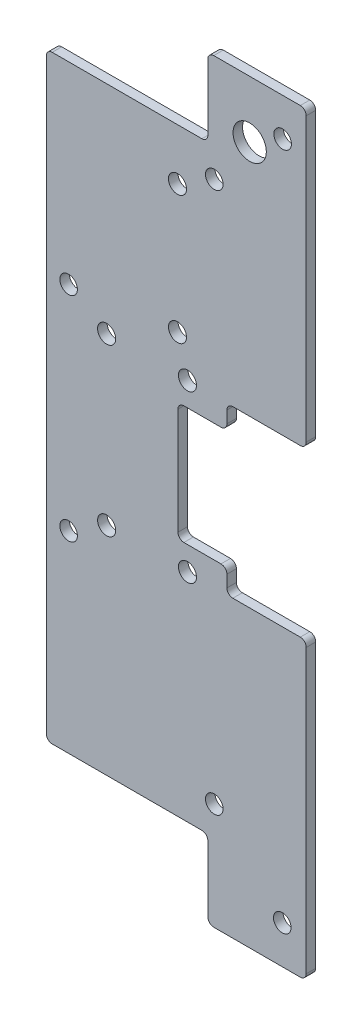
SolidWorks part; units mm, degrees
material "Thornel Mat VMA"
ref_plane "Front Plane" through (0, 0, 0) normal (0, 0, 1) x (1, 0, 0)
ref_plane "Top Plane" through (0, 0, 0) normal (0, 1, 0) x (1, 0, 0)
ref_plane "Right Plane" through (0, 0, 0) normal (1, 0, 0) x (0, 0, -1)
sketch "Sketch1" plane through (0, 0, 0) normal (0, 0, 1) x (1, 0, 0)
  line L0 (-2.9301, -104.5098) -> (-3.3149, -104.5098)
  line L1 (-3.3149, -72.8868) -> (-2.9301, -72.8868)
  line L78 (45.3299, -66.5368) -> (45.3299, -72.8868)
  line L79 (45.3299, -104.5098) -> (45.3299, -110.8598)
  line L80 (66.5174, -66.5368) -> (105.3971, 12.1397)
  line L81 (105.3971, 12.1397) -> (38.7094, 12.1397)
  line L88 (38.7094, 12.1397) -> (38.7094, -8.6883)
  line L89 (-2.9301, -8.6883) -> (38.7094, -8.6883)
  line L90 (-3.3149, -53.8368) -> (-2.9301, -53.8368)
  line L91 (-2.9301, -53.8368) -> (-2.9301, -8.6883)
  line L92 (-3.3149, -66.5368) -> (-3.3149, -53.8368)
  line L93 (-3.3149, -72.8868) -> (-3.3149, -66.5368)
  line L94 (-2.9301, -104.5098) -> (-2.9301, -72.8868)
  line L95 (-3.3149, -110.8598) -> (-3.3149, -104.5098)
  line L96 (66.5174, -110.8598) -> (105.3971, -189.5363)
  line L97 (105.3971, -189.5363) -> (38.7094, -189.5363)
  line L98 (38.7094, -189.5363) -> (38.7094, -168.7083)
  line L99 (-2.9301, -168.7083) -> (38.7094, -168.7083)
  line L106 (-3.3149, -110.8598) -> (-3.3149, -123.5598)
  line L107 (-3.3149, -123.5598) -> (-2.9301, -123.5598)
  line L108 (66.5174, -110.8598) -> (45.3299, -110.8598)
  line L109 (45.3299, -66.5368) -> (66.5174, -66.5368)
  line L110 (45.3299, -104.5098) -> (45.3299, -72.8868)
  line L111 (-2.9301, -123.5598) -> (-2.9301, -168.7083)
  circle A0 centre (90.6739, 2.6147) radius 2.3495
  circle A1 centre (41.9566, -16.4353) radius 2.3495
  circle A2 centre (3.0351, -60.1868) radius 2.3495
  circle A3 centre (3.0351, -117.2098) radius 2.3495
  circle A4 centre (41.9566, -160.9613) radius 2.3495
  circle A5 centre (90.6739, -180.0113) radius 2.3495
  circle A6 centre (51.4094, -3.1003) radius 4.445
  point P2 (90.6739, 2.6147)
  point P4 (41.9566, -16.4353)
  point P6 (3.0351, -60.1868)
  point P8 (3.0351, -117.2098)
  point P10 (41.9566, -160.9613)
  point P11 (90.6739, -180.0113)
  dimension "D2" = 4.699
  dimension "D5" = 8.89
  dimension "D1" = 66.6876
  dimension "D3" = 12.7
  dimension "D4" = 15.24
  dimension "D6" = 48.26
extrude "Boss-Extrude1" add sketch "Sketch1" along normal blind 2.54
sketch "Sketch2" plane through (0, 0, 2.54) normal (0, 0, 1) x (1, 0, 0)
  line L0 (-3.3149, -53.8368) -> (-3.3149, -72.8868) construction
  line L1 (45.3299, -66.5368) -> (66.5174, -66.5368) construction
  line L2 (45.3299, -88.6983) -> (-2.9301, -88.6983) construction
  line L3 (45.3299, -110.8598) -> (45.3299, -66.5368) construction
  line L4 (-2.9301, -72.8868) -> (-2.9301, -104.5098) construction
  circle A0 centre (13.1951, -66.5368) radius 2.413
  circle A2 centre (34.7851, -66.5368) radius 2.413
  circle A4 centre (34.7851, -110.8598) radius 2.413
  circle A6 centre (13.1951, -110.8598) radius 2.413
  dimension "D1" = 4.826
  dimension "D2" = 21.59
  dimension "D3" = 4.826
  dimension "D5" = 16.51
  dimension "D7" = 0
extrude "Cut-Extrude1" cut sketch "Sketch2" against normal through all
sketch "Sketch3" plane through (0, 0, 2.54) normal (0, 0, 1) x (1, 0, 0)
  line L0 (45.3299, -110.8598) -> (45.3299, -66.5368) construction
  line L1 (45.3299, -72.8868) -> (32.2451, -72.8868)
  line L2 (45.3299, -72.8868) -> (45.3299, -104.5098)
  line L3 (45.3299, -104.5098) -> (32.2451, -104.5098)
  line L4 (32.2451, -72.8868) -> (32.2451, -104.5098)
  line L5 (45.3299, -66.5368) -> (66.5174, -66.5368) construction
  line L6 (66.5174, -110.8598) -> (45.3299, -110.8598) construction
  circle A1 centre (13.1951, -66.5368) radius 2.413 construction
  dimension "D3" = 19.05
  dimension "D1" = 6.35
  dimension "D2" = 6.35
extrude "Cut-Extrude2" cut sketch "Sketch3" against normal through all
sketch "Sketch4" plane through (0, 0, 2.54) normal (0, 0, 1) x (1, 0, 0)
  line L0 (-2.9301, -168.7083) -> (38.7094, -168.7083) construction
  line L1 (27.4577, 15.7469) -> (40.2334, 15.7469)
  line L2 (27.4577, 15.7469) -> (27.4577, -8.6883)
  line L3 (27.4577, -8.6883) -> (40.2334, -8.6883)
  line L4 (40.2334, 15.7469) -> (40.2334, -8.6883)
  line L5 (0, -197.042) -> (40.2334, -197.042)
  line L6 (0, -197.042) -> (0, -168.7083)
  line L7 (0, -168.7083) -> (40.2334, -168.7083)
  line L8 (40.2334, -197.042) -> (40.2334, -168.7083)
  line L9 (38.7094, -168.7083) -> (38.7094, -189.5363) construction
  line L10 (38.7094, -8.6883) -> (-2.9301, -8.6883) construction
  dimension "D1" = 1.524
extrude "Cut-Extrude3" cut sketch "Sketch4" against normal through all
sketch "Sketch5" plane through (0, 0, 0) normal (0, 0, -1) x (-1, 0, 0)
  line L0 (2.9301, -8.6883) -> (2.9301, -53.8368) construction
  line L1 (-40.2334, -8.6883) -> (2.9301, -8.6883) construction
  circle A0 centre (-32.1219, -22.4043) radius 2.413
  circle A1 centre (-32.1219, -56.6943) radius 2.413
  dimension "D4" = 4.826
  dimension "D1" = 35.052
  dimension "D2" = 13.716
  dimension "D3" = 34.29
extrude "Cut-Extrude4" cut sketch "Sketch5" against normal through all
sketch "Sketch7" plane through (0, 0, 2.54) normal (0, 0, 1) x (1, 0, 0)
  line L0 (66.5174, -66.5368) -> (66.5174, 21.5221)
  line L1 (66.5174, 21.5221) -> (127.8208, 21.5221)
  line L2 (66.5174, -110.8598) -> (66.5174, -200.2563)
  line L3 (66.5174, -200.2563) -> (115.7822, -200.2563)
  line L4 (115.7822, -200.2563) -> (127.8208, 21.5221)
  line L5 (66.5174, -66.5368) -> (66.5174, -110.8598)
extrude "Cut-Extrude5" cut sketch "Sketch7" against normal through all both and the other way through all
extrude "Cut-Extrude6" cut sketch "Sketch8" against normal through all
sketch "Sketch8" plane through (13.5516, -170.5467, 0) normal (0, 0, -1) x (0.9999, -0.0134, 0)
  circle A0 centre (44.3535, -173.1756) radius 2.3495
  circle A1 centre (46.6818, 8.1643) radius 2.3495
fillet "Fillet1" radius 1.5875 16 edges at (-2.9301, -168.7083, 1.27) (40.2334, -168.7083, 1.27) (40.2334, -189.5363, 1.27) (66.5174, -189.5363, 1.27) (66.5174, -110.8598, 1.27) (45.3299, -110.8598, 1.27) (45.3299, -104.5098, 1.27) (32.2451, -104.5098, 1.27) (32.2451, -72.8868, 1.27) (45.3299, -72.8868, 1.27) (45.3299, -66.5368, 1.27) (66.5174, -66.5368, 1.27) (66.5174, 12.1397, 1.27) (40.2334, 12.1397, 1.27) (40.2334, -8.6883, 1.27) (-2.9301, -8.6883, 1.27)
sketch "Sketch9" plane through (0, -123.5598, 0) normal (0, -1, 0) x (1, 0, 0)
  line L1 (-3.3149, 2.54) -> (-2.9301, 2.54)
  line L2 (-3.3149, 2.54) -> (-3.3149, 0)
  line L3 (-3.3149, 0) -> (-2.9301, 0)
  line L4 (-2.9301, 2.54) -> (-2.9301, 0)
extrude "Cut-Extrude7" cut sketch "Sketch9" against normal through all
